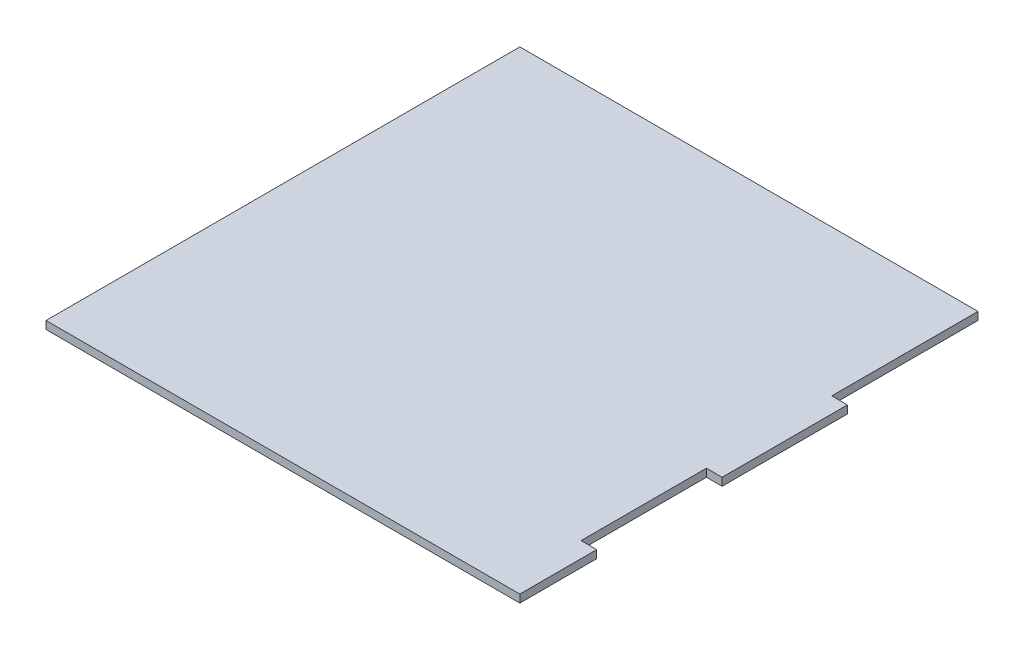
SolidWorks part; units mm, degrees
ref_plane "Front Plane" through (0, 0, 0) normal (0, 0, 1) x (1, 0, 0)
ref_plane "Top Plane" through (0, 0, 0) normal (0, 1, 0) x (1, 0, 0)
ref_plane "Right Plane" through (0, 0, 0) normal (1, 0, 0) x (0, 0, -1)
sketch "Sketch1" plane through (0, 0, 0) normal (0, 1, 0) x (1, 0, 0)
  line L0 (192, 31.16) -> (185.65, 31.16) construction
  line L1 (0, 0) -> (192, 0)
  line L2 (0, 0) -> (0, 192)
  line L3 (0, 192) -> (185.65, 192)
  line L4 (192, 0) -> (192, 31.16)
  line L5 (0, 0) -> (185.65, 185.65) construction
  line L6 (0, 192) -> (192, 0) construction
  line L7 (185.65, 31.16) -> (185.65, 81.96) construction
  line L8 (192, 81.96) -> (185.65, 81.96) construction
  line L9 (192, 132.76) -> (185.65, 132.76) construction
  line L10 (185.65, 132.76) -> (185.65, 195.2701) construction
  line L11 (192, 31.16) -> (185.65, 31.16)
  line L12 (185.65, 31.16) -> (185.65, 81.96)
  line L13 (192, 81.96) -> (185.65, 81.96)
  line L14 (192, 132.76) -> (185.65, 132.76)
  line L15 (185.65, 132.76) -> (185.65, 192)
  line L16 (192, 81.96) -> (192, 132.76)
  point P4 (96, 96)
  dimension "D2" = 192
extrude "Boss-Extrude1" add sketch "Sketch1" along normal blind 3.175
